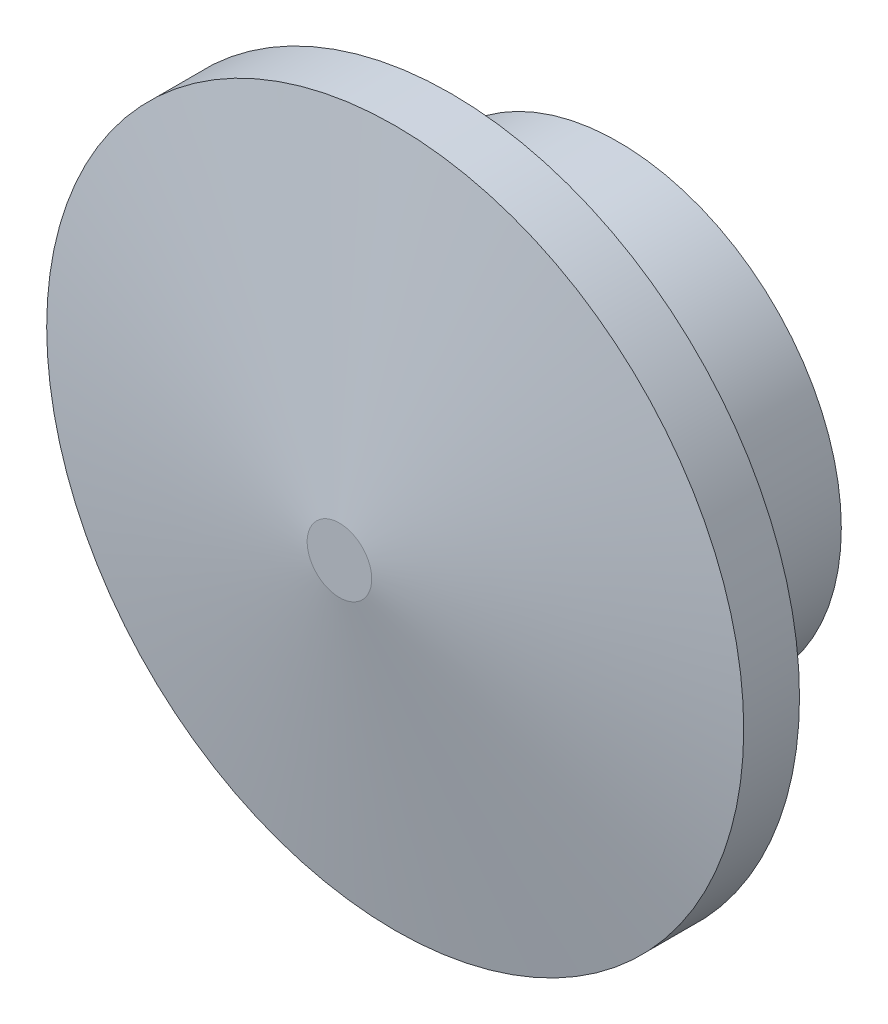
SolidWorks part; units mm, degrees
ref_plane "Front Plane" through (0, 0, 0) normal (0, 0, 1) x (1, 0, 0)
ref_plane "Top Plane" through (0, 0, 0) normal (0, 1, 0) x (1, 0, 0)
ref_plane "Right Plane" through (0, 0, 0) normal (1, 0, 0) x (0, 0, -1)
sketch "Sketch1" plane through (0, 0, 0) normal (0, 0, 1) x (1, 0, 0)
  line L0 (0, -44.5788) -> (0, 47.9169) construction
  line L1 (53.8578, 0) -> (-57.3712, 0) construction
  circle A0 centre (0, 0) radius 8
sketch "Sketch2" plane through (0, 0, 0) normal (0, 1, 0) x (1, 0, 0)
  line L0 (0, 172.8456) -> (0, -46.9914) construction
extrude "Boss-Extrude2" add sketch "Sketch1" against normal blind 6
sketch "Sketch5" plane through (0, 0, 0) normal (0, 0, 1) x (1, 0, 0)
  circle A0 centre (0, 0) radius 12.5
extrude "Boss-Extrude3" add sketch "Sketch5" along normal blind 2
sketch "Sketch6" plane through (0, 0, 2) normal (0, 0, 1) x (1, 0, 0)
  circle A1 centre (0, 0) radius 12.5
extrude "Boss-Extrude4" add sketch "Sketch6" along normal blind 2 draft 80
sketch "Sketch7" plane through (0, 0, -6) normal (0, 0, -1) x (-1, 0, 0)
  circle A0 centre (0, 0) radius 8
